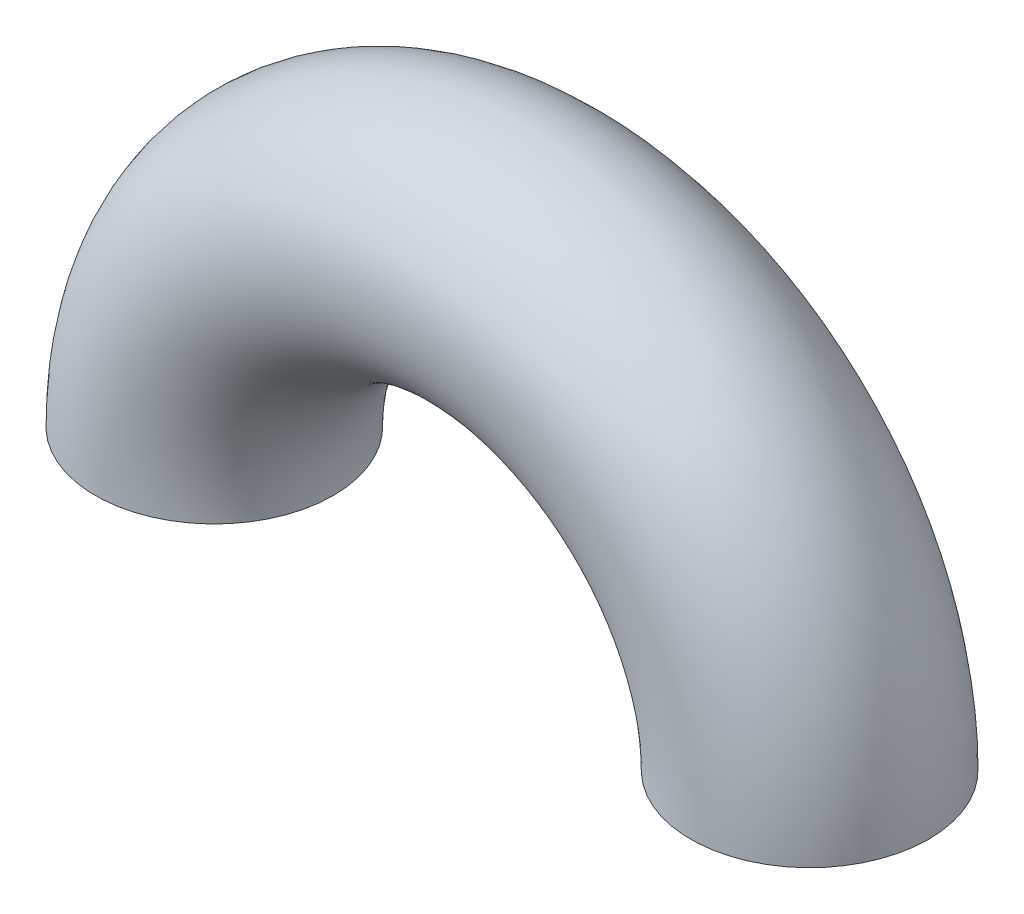
SolidWorks part; units mm, degrees
material "Copper-Cobalt-Beryllium alloy, UNS C17500"
ref_plane "Front Plane" through (0, 0, 0) normal (0, 0, 1) x (1, 0, 0)
ref_plane "Top Plane" through (0, 0, 0) normal (0, 1, 0) x (1, 0, 0)
ref_plane "Right Plane" through (0, 0, 0) normal (1, 0, 0) x (0, 0, -1)
sketch "Sketch2" plane through (0, 0, 0) normal (0, 1, 0) x (1, 0, 0)
  circle A0 centre (0, 0) radius 5
  dimension "D1" = 10
sketch "Sketch3" plane through (0, 0, 0) normal (0, 0, 1) x (1, 0, 0)
  arc A0 (0, 0) -> (25, 0) centre (12.5, 0) cw
  dimension "D1" = 12.5
sweep "Sweep1" add profiles "Sketch2" path "Sketch3"
shell "Shell1" thickness 0.5
